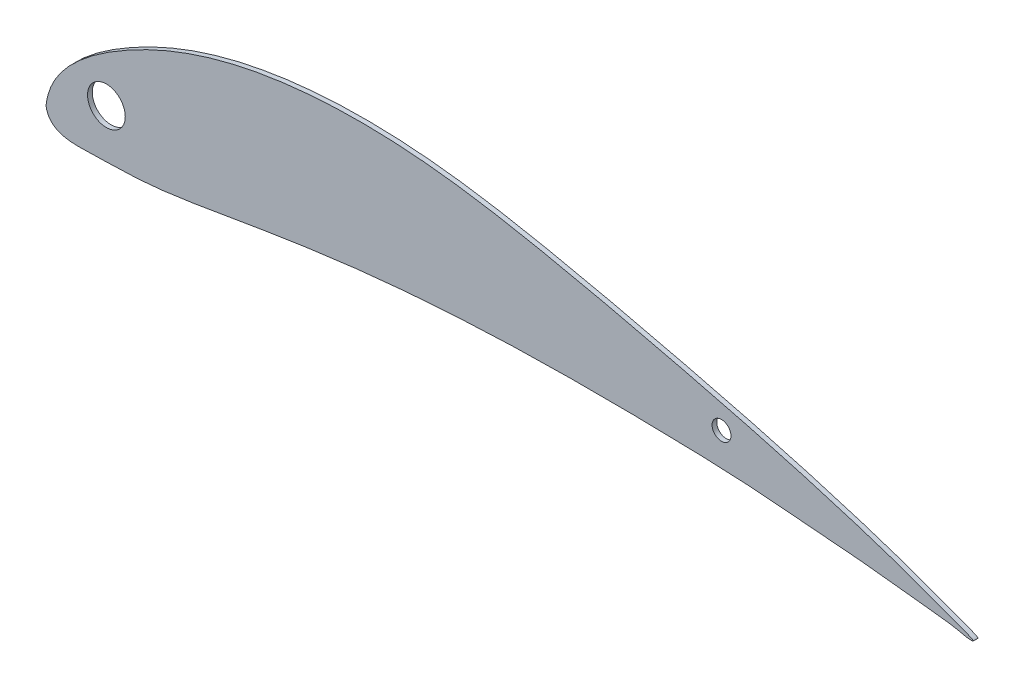
SolidWorks part; units mm, degrees
ref_plane "Front Plane" through (0, 0, 0) normal (0, 0, 1) x (1, 0, 0)
ref_plane "Top Plane" through (0, 0, 0) normal (0, 1, 0) x (1, 0, 0)
ref_plane "Right Plane" through (0, 0, 0) normal (1, 0, 0) x (0, 0, -1)
sketch "Sketch1" plane through (0, 0, 0) normal (0, 0, 1) x (1, 0, 0)
  spline S0 degree 3 poles (0.0006, 0.0001) (0.8106, 7.3592) (8.6491, 17.8566) (26.2867, 29.9752) (52.1111, 42.0692) (89.5976, 49.2908) (131.4008, 47.8848) (173.2567, 40.0411) (217.9611, 29.613) (256.9521, 19.5289) (290.3598, 8.711) (301.2732, 4.3828) (314.8169, -0.5162) (309.8463, 0.0001) knots 0 0 0 0 0.060864 0.113688 0.188609 0.312909 0.448482 0.557612 0.691544 0.852438 0.929756 0.976058 1 1 1 1
  spline S1 degree 3 poles (309.8463, 0.0001) (303.9568, 1.471) (293.9895, 2.094) (276.264, 4.5144) (260.8463, 5.4274) (235.8588, 7.8703) (205.1014, 8.8381) (157.7186, 9.0307) (110.4973, 6.1815) (66.5062, -0.5867) (36.4547, -6.0985) (15.3166, -6.1891) (1.2307, -6.9241) (0.0006, 0.0001) knots 0 0 0 0 0.057787 0.095275 0.171021 0.205339 0.335319 0.464904 0.658702 0.785512 0.893517 0.943092 1 1 1 1
extrude "Boss-Extrude1" add sketch "Sketch1" along normal blind 1.5875
sketch "Sketch2" plane through (0, 0, 1.5875) normal (0, 0, 1) x (1, 0, 0)
  circle A0 centre (20.32, 10.16) radius 6.35
  circle A1 centre (227.2963, 19.0501) radius 3.175
  dimension "D2" = 12.7
  dimension "D3" = 6.35
  dimension "D6" = 20.32
  dimension "D1" = 82.55
  dimension "D4" = 19.05
  dimension "D5" = 10.16
extrude "Cut-Extrude1" cut sketch "Sketch2" against normal through all
